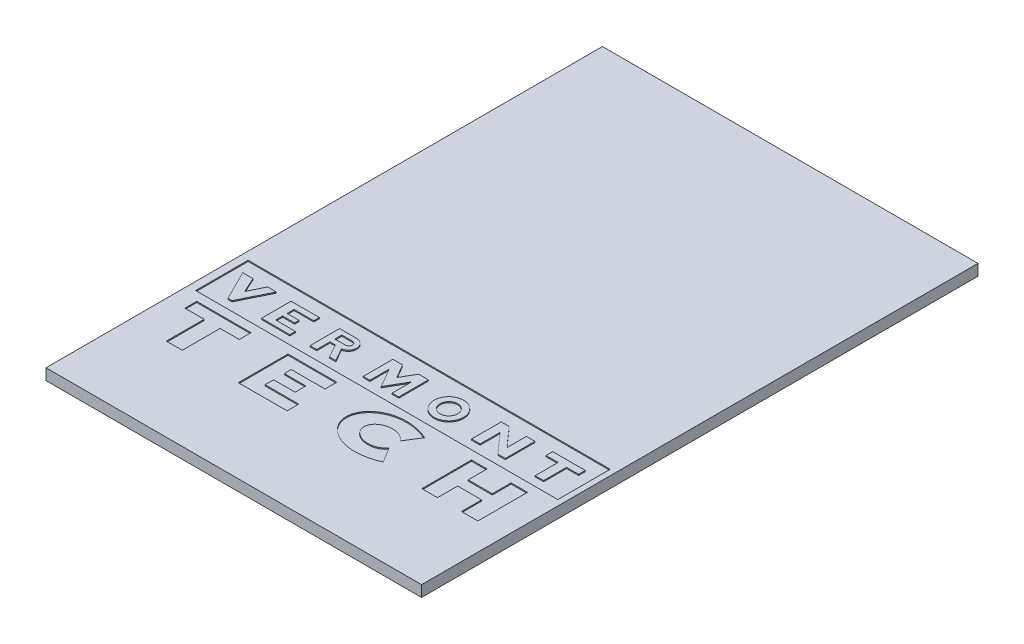
SolidWorks part; units mm, degrees
ref_plane "Front Plane" through (0, 0, 0) normal (0, 0, 1) x (1, 0, 0)
ref_plane "Top Plane" through (0, 0, 0) normal (0, 1, 0) x (1, 0, 0)
ref_plane "Right Plane" through (0, 0, 0) normal (1, 0, 0) x (0, 0, -1)
sketch "Sketch1" plane through (0, 0, 0) normal (0, 1, 0) x (1, 0, 0)
  line L1 (-42.8625, -63.5) -> (42.8625, -63.5) construction
  line L2 (-42.8625, -63.5) -> (-42.8625, 63.5) construction
  line L3 (-42.8625, 63.5) -> (42.8625, 63.5) construction
  line L4 (42.8625, -63.5) -> (42.8625, 63.5) construction
  line L5 (-42.8625, -63.5) -> (42.8625, 63.5) construction
  line L6 (-42.8625, 63.5) -> (42.8625, -63.5) construction
  line L7 (0, 0) -> (0, 63.5) construction
  point P0 (0, 0)
  dimension "D1" = 85.725
  dimension "D2" = 127
sketch "Sketch2" plane through (0, 0, 0) normal (0, 1, 0) x (1, 0, 0)
  line L0 (-42.8625, -63.5) -> (-42.8625, 63.5) construction
  line L1 (-42.8625, 63.5) -> (42.8625, 63.5) construction
  line L2 (42.8625, -63.5) -> (42.8625, 63.5) construction
  line L3 (-42.8625, -63.5) -> (42.8625, -63.5) construction
  line L4 (-42.8625, -63.5) -> (-42.8625, 63.5)
  line L5 (-42.8625, 63.5) -> (42.8625, 63.5)
  line L6 (42.8625, -63.5) -> (42.8625, 63.5)
  line L7 (-42.8625, -63.5) -> (42.8625, -63.5)
extrude "Boss-Extrude2" add sketch "Sketch2" against normal blind 2.54
sketch "Sketch17" plane through (0, 0, 0) normal (0, 1, 0) x (1, 0, 0)
  line L0 (-29.0853, 54.0966) -> (-29.424, 55.1126)
  line L1 (-29.424, 55.1126) -> (-30.1013, 56.0608)
  line L2 (-30.1013, 56.0608) -> (-30.7109, 56.535)
  line L3 (-30.7109, 56.535) -> (-31.9978, 56.535)
  line L4 (-31.9978, 56.535) -> (-32.6752, 56.0608)
  line L5 (-32.6752, 56.0608) -> (-33.2848, 55.1126)
  line L6 (-33.2848, 55.1126) -> (-33.6234, 54.0966)
  line L7 (-33.6234, 54.0966) -> (-33.9621, 52.6742)
  line L8 (-33.9621, 52.6742) -> (-33.9621, 50.2358)
  line L9 (-33.9621, 50.2358) -> (-33.6234, 48.8134)
  line L10 (-33.6234, 48.8134) -> (-33.2848, 47.7974)
  line L11 (-33.2848, 47.7974) -> (-32.6752, 46.8491)
  line L12 (-32.6752, 46.8491) -> (-31.9978, 46.375)
  line L13 (-31.9978, 46.375) -> (-30.7109, 46.375)
  line L14 (-30.7109, 46.375) -> (-30.1013, 46.8491)
  line L15 (-30.1013, 46.8491) -> (-29.424, 47.7974)
  line L16 (-29.424, 47.7974) -> (-29.0853, 48.8134)
  line L17 (-23.328, 53.1483) -> (-23.328, 46.375)
  line L18 (-23.328, 51.7259) -> (-23.9376, 52.6742)
  line L19 (-23.9376, 52.6742) -> (-24.6149, 53.1483)
  line L20 (-24.6149, 53.1483) -> (-25.5632, 53.1483)
  line L21 (-25.5632, 53.1483) -> (-26.1728, 52.6742)
  line L22 (-26.1728, 52.6742) -> (-26.8501, 51.7259)
  line L23 (-26.8501, 51.7259) -> (-27.1888, 50.2358)
  line L24 (-27.1888, 50.2358) -> (-27.1888, 49.2875)
  line L25 (-27.1888, 49.2875) -> (-26.8501, 47.7974)
  line L26 (-26.8501, 47.7974) -> (-26.1728, 46.8491)
  line L27 (-26.1728, 46.8491) -> (-25.5632, 46.375)
  line L28 (-25.5632, 46.375) -> (-24.6149, 46.375)
  line L29 (-24.6149, 46.375) -> (-23.9376, 46.8491)
  line L30 (-23.9376, 46.8491) -> (-23.328, 47.7974)
  line L31 (-20.7541, 53.1483) -> (-20.7541, 46.375)
  line L32 (-20.7541, 50.2358) -> (-20.4154, 51.7259)
  line L33 (-20.4154, 51.7259) -> (-19.8058, 52.6742)
  line L34 (-19.8058, 52.6742) -> (-19.1285, 53.1483)
  line L35 (-19.1285, 53.1483) -> (-18.1802, 53.1483)
  line L36 (-16.216, 56.535) -> (-16.216, 48.3392)
  line L37 (-16.216, 48.3392) -> (-15.8773, 46.8491)
  line L38 (-15.8773, 46.8491) -> (-15.2677, 46.375)
  line L39 (-15.2677, 46.375) -> (-14.5904, 46.375)
  line L40 (-17.1642, 53.1483) -> (-14.929, 53.1483)
  line L41 (-13.0325, 50.2358) -> (-9.1717, 50.2358)
  line L42 (-9.1717, 50.2358) -> (-9.1717, 51.184)
  line L43 (-9.1717, 51.184) -> (-9.4426, 52.2)
  line L44 (-9.4426, 52.2) -> (-9.7813, 52.6742)
  line L45 (-9.7813, 52.6742) -> (-10.4586, 53.1483)
  line L46 (-10.4586, 53.1483) -> (-11.4069, 53.1483)
  line L47 (-11.4069, 53.1483) -> (-12.0165, 52.6742)
  line L48 (-12.0165, 52.6742) -> (-12.6938, 51.7259)
  line L49 (-12.6938, 51.7259) -> (-13.0325, 50.2358)
  line L50 (-13.0325, 50.2358) -> (-13.0325, 49.2875)
  line L51 (-13.0325, 49.2875) -> (-12.6938, 47.7974)
  line L52 (-12.6938, 47.7974) -> (-12.0165, 46.8491)
  line L53 (-12.0165, 46.8491) -> (-11.4069, 46.375)
  line L54 (-11.4069, 46.375) -> (-10.4586, 46.375)
  line L55 (-10.4586, 46.375) -> (-9.7813, 46.8491)
  line L56 (-9.7813, 46.8491) -> (-9.1717, 47.7974)
  line L57 (-6.8688, 53.1483) -> (-6.8688, 46.375)
  line L58 (-6.8688, 50.2358) -> (-6.5301, 51.7259)
  line L59 (-6.5301, 51.7259) -> (-5.9205, 52.6742)
  line L60 (-5.9205, 52.6742) -> (-5.2432, 53.1483)
  line L61 (-5.2432, 53.1483) -> (-4.2949, 53.1483)
  line L62 (2.4784, 56.535) -> (2.4784, 46.375)
  line L63 (2.4784, 56.535) -> (5.0523, 46.375)
  line L64 (7.6262, 56.535) -> (5.0523, 46.375)
  line L65 (7.6262, 56.535) -> (7.6262, 46.375)
  line L66 (9.8614, 50.2358) -> (13.7222, 50.2358)
  line L67 (13.7222, 50.2358) -> (13.7222, 51.184)
  line L68 (13.7222, 51.184) -> (13.4512, 52.2)
  line L69 (13.4512, 52.2) -> (13.1126, 52.6742)
  line L70 (13.1126, 52.6742) -> (12.4352, 53.1483)
  line L71 (12.4352, 53.1483) -> (11.487, 53.1483)
  line L72 (11.487, 53.1483) -> (10.8774, 52.6742)
  line L73 (10.8774, 52.6742) -> (10.2, 51.7259)
  line L74 (10.2, 51.7259) -> (9.8614, 50.2358)
  line L75 (9.8614, 50.2358) -> (9.8614, 49.2875)
  line L76 (9.8614, 49.2875) -> (10.2, 47.7974)
  line L77 (10.2, 47.7974) -> (10.8774, 46.8491)
  line L78 (10.8774, 46.8491) -> (11.487, 46.375)
  line L79 (11.487, 46.375) -> (12.4352, 46.375)
  line L80 (12.4352, 46.375) -> (13.1126, 46.8491)
  line L81 (13.1126, 46.8491) -> (13.7222, 47.7974)
  line L82 (19.5472, 53.1483) -> (19.5472, 46.375)
  line L83 (19.5472, 51.7259) -> (18.9376, 52.6742)
  line L84 (18.9376, 52.6742) -> (18.2603, 53.1483)
  line L85 (18.2603, 53.1483) -> (17.312, 53.1483)
  line L86 (17.312, 53.1483) -> (16.7024, 52.6742)
  line L87 (16.7024, 52.6742) -> (16.0251, 51.7259)
  line L88 (16.0251, 51.7259) -> (15.6864, 50.2358)
  line L89 (15.6864, 50.2358) -> (15.6864, 49.2875)
  line L90 (15.6864, 49.2875) -> (16.0251, 47.7974)
  line L91 (16.0251, 47.7974) -> (16.7024, 46.8491)
  line L92 (16.7024, 46.8491) -> (17.312, 46.375)
  line L93 (17.312, 46.375) -> (18.2603, 46.375)
  line L94 (18.2603, 46.375) -> (18.9376, 46.8491)
  line L95 (18.9376, 46.8491) -> (19.5472, 47.7974)
  line L96 (22.1211, 56.535) -> (22.1211, 46.375)
  line L97 (24.3563, 50.2358) -> (28.2171, 50.2358)
  line L98 (28.2171, 50.2358) -> (28.2171, 51.184)
  line L99 (28.2171, 51.184) -> (27.9462, 52.2)
  line L100 (27.9462, 52.2) -> (27.6075, 52.6742)
  line L101 (27.6075, 52.6742) -> (26.9302, 53.1483)
  line L102 (26.9302, 53.1483) -> (25.9819, 53.1483)
  line L103 (25.9819, 53.1483) -> (25.3723, 52.6742)
  line L104 (25.3723, 52.6742) -> (24.695, 51.7259)
  line L105 (24.695, 51.7259) -> (24.3563, 50.2358)
  line L106 (24.3563, 50.2358) -> (24.3563, 49.2875)
  line L107 (24.3563, 49.2875) -> (24.695, 47.7974)
  line L108 (24.695, 47.7974) -> (25.3723, 46.8491)
  line L109 (25.3723, 46.8491) -> (25.9819, 46.375)
  line L110 (25.9819, 46.375) -> (26.9302, 46.375)
  line L111 (26.9302, 46.375) -> (27.6075, 46.8491)
  line L112 (27.6075, 46.8491) -> (28.2171, 47.7974)
  line L113 (29.9104, 53.1483) -> (31.807, 46.375)
  line L114 (33.7712, 53.1483) -> (31.807, 46.375)
  line L115 (31.807, 46.375) -> (31.1974, 44.4107)
  line L116 (31.1974, 44.4107) -> (30.52, 43.4624)
  line L117 (30.52, 43.4624) -> (29.9104, 43.056)
  line L118 (29.9104, 43.056) -> (29.5718, 43.056)
sketch "Sketch18" plane through (0, 0, 0) normal (0, 1, 0) x (1, 0, 0)
  line L0 (-30.7518, 39.376) -> (-30.7518, 29.216)
  line L1 (-30.7518, 39.376) -> (-27.8392, 39.376)
  line L2 (-27.8392, 39.376) -> (-26.891, 38.9019)
  line L3 (-26.891, 38.9019) -> (-26.5523, 38.4277)
  line L4 (-26.5523, 38.4277) -> (-26.2136, 37.4117)
  line L5 (-26.2136, 37.4117) -> (-26.2136, 36.4635)
  line L6 (-26.2136, 36.4635) -> (-26.5523, 35.5152)
  line L7 (-26.5523, 35.5152) -> (-26.891, 35.0411)
  line L8 (-26.891, 35.0411) -> (-27.8392, 34.5669)
  line L9 (-30.7518, 34.5669) -> (-27.8392, 34.5669)
  line L10 (-27.8392, 34.5669) -> (-26.891, 34.0251)
  line L11 (-26.891, 34.0251) -> (-26.5523, 33.5509)
  line L12 (-26.5523, 33.5509) -> (-26.2136, 32.6027)
  line L13 (-26.2136, 32.6027) -> (-26.2136, 31.1803)
  line L14 (-26.2136, 31.1803) -> (-26.5523, 30.1643)
  line L15 (-26.5523, 30.1643) -> (-26.891, 29.6901)
  line L16 (-26.891, 29.6901) -> (-27.8392, 29.216)
  line L17 (-27.8392, 29.216) -> (-30.7518, 29.216)
  line L18 (-24.3171, 33.0768) -> (-20.4563, 33.0768)
  line L19 (-20.4563, 33.0768) -> (-20.4563, 34.0251)
  line L20 (-20.4563, 34.0251) -> (-20.7272, 35.0411)
  line L21 (-20.7272, 35.0411) -> (-21.0659, 35.5152)
  line L22 (-21.0659, 35.5152) -> (-21.7432, 35.9893)
  line L23 (-21.7432, 35.9893) -> (-22.6915, 35.9893)
  line L24 (-22.6915, 35.9893) -> (-23.3011, 35.5152)
  line L25 (-23.3011, 35.5152) -> (-23.9784, 34.5669)
  line L26 (-23.9784, 34.5669) -> (-24.3171, 33.0768)
  line L27 (-24.3171, 33.0768) -> (-24.3171, 32.1285)
  line L28 (-24.3171, 32.1285) -> (-23.9784, 30.6384)
  line L29 (-23.9784, 30.6384) -> (-23.3011, 29.6901)
  line L30 (-23.3011, 29.6901) -> (-22.6915, 29.216)
  line L31 (-22.6915, 29.216) -> (-21.7432, 29.216)
  line L32 (-21.7432, 29.216) -> (-21.0659, 29.6901)
  line L33 (-21.0659, 29.6901) -> (-20.4563, 30.6384)
  line L34 (-18.1534, 35.9893) -> (-18.1534, 29.216)
  line L35 (-18.1534, 34.0251) -> (-17.2051, 35.5152)
  line L36 (-17.2051, 35.5152) -> (-16.5278, 35.9893)
  line L37 (-16.5278, 35.9893) -> (-15.5795, 35.9893)
  line L38 (-15.5795, 35.9893) -> (-14.9022, 35.5152)
  line L39 (-14.9022, 35.5152) -> (-14.6312, 34.0251)
  line L40 (-14.6312, 34.0251) -> (-14.6312, 29.216)
  line L41 (-6.9096, 39.376) -> (-6.9096, 29.216)
  line L42 (-2.3715, 39.376) -> (-2.3715, 29.216)
  line L43 (-6.9096, 34.5669) -> (-2.3715, 34.5669)
  line L44 (1.4893, 35.9893) -> (0.8797, 35.5152)
  line L45 (0.8797, 35.5152) -> (0.2024, 34.5669)
  line L46 (0.2024, 34.5669) -> (-0.1363, 33.0768)
  line L47 (-0.1363, 33.0768) -> (-0.1363, 32.1285)
  line L48 (-0.1363, 32.1285) -> (0.2024, 30.6384)
  line L49 (0.2024, 30.6384) -> (0.8797, 29.6901)
  line L50 (0.8797, 29.6901) -> (1.4893, 29.216)
  line L51 (1.4893, 29.216) -> (2.4376, 29.216)
  line L52 (2.4376, 29.216) -> (3.1149, 29.6901)
  line L53 (3.1149, 29.6901) -> (3.7245, 30.6384)
  line L54 (3.7245, 30.6384) -> (4.0632, 32.1285)
  line L55 (4.0632, 32.1285) -> (4.0632, 33.0768)
  line L56 (4.0632, 33.0768) -> (3.7245, 34.5669)
  line L57 (3.7245, 34.5669) -> (3.1149, 35.5152)
  line L58 (3.1149, 35.5152) -> (2.4376, 35.9893)
  line L59 (2.4376, 35.9893) -> (1.4893, 35.9893)
  line L60 (6.2984, 39.376) -> (6.2984, 29.216)
  line L61 (8.8722, 39.376) -> (8.8722, 29.216)
  line L62 (11.1074, 33.0768) -> (14.9682, 33.0768)
  line L63 (14.9682, 33.0768) -> (14.9682, 34.0251)
  line L64 (14.9682, 34.0251) -> (14.6973, 35.0411)
  line L65 (14.6973, 35.0411) -> (14.3586, 35.5152)
  line L66 (14.3586, 35.5152) -> (13.6813, 35.9893)
  line L67 (13.6813, 35.9893) -> (12.733, 35.9893)
  line L68 (12.733, 35.9893) -> (12.1234, 35.5152)
  line L69 (12.1234, 35.5152) -> (11.4461, 34.5669)
  line L70 (11.4461, 34.5669) -> (11.1074, 33.0768)
  line L71 (11.1074, 33.0768) -> (11.1074, 32.1285)
  line L72 (11.1074, 32.1285) -> (11.4461, 30.6384)
  line L73 (11.4461, 30.6384) -> (12.1234, 29.6901)
  line L74 (12.1234, 29.6901) -> (12.733, 29.216)
  line L75 (12.733, 29.216) -> (13.6813, 29.216)
  line L76 (13.6813, 29.216) -> (14.3586, 29.6901)
  line L77 (14.3586, 29.6901) -> (14.9682, 30.6384)
  line L78 (17.2712, 35.9893) -> (17.2712, 29.216)
  line L79 (17.2712, 33.0768) -> (17.6098, 34.5669)
  line L80 (17.6098, 34.5669) -> (18.2194, 35.5152)
  line L81 (18.2194, 35.5152) -> (18.8968, 35.9893)
  line L82 (18.8968, 35.9893) -> (19.845, 35.9893)
  line L83 (24.9928, 35.9893) -> (24.9928, 29.216)
  line L84 (24.9928, 34.5669) -> (24.3832, 35.5152)
  line L85 (24.3832, 35.5152) -> (23.7058, 35.9893)
  line L86 (23.7058, 35.9893) -> (22.7576, 35.9893)
  line L87 (22.7576, 35.9893) -> (22.148, 35.5152)
  line L88 (22.148, 35.5152) -> (21.4706, 34.5669)
  line L89 (21.4706, 34.5669) -> (21.132, 33.0768)
  line L90 (21.132, 33.0768) -> (21.132, 32.1285)
  line L91 (21.132, 32.1285) -> (21.4706, 30.6384)
  line L92 (21.4706, 30.6384) -> (22.148, 29.6901)
  line L93 (22.148, 29.6901) -> (22.7576, 29.216)
  line L94 (22.7576, 29.216) -> (23.7058, 29.216)
  line L95 (23.7058, 29.216) -> (24.3832, 29.6901)
  line L96 (24.3832, 29.6901) -> (24.9928, 30.6384)
  line L97 (27.5666, 35.9893) -> (27.5666, 29.216)
  line L98 (27.5666, 34.0251) -> (28.5149, 35.5152)
  line L99 (28.5149, 35.5152) -> (29.1922, 35.9893)
  line L100 (29.1922, 35.9893) -> (30.1405, 35.9893)
  line L101 (30.1405, 35.9893) -> (30.8178, 35.5152)
  line L102 (30.8178, 35.5152) -> (31.0888, 34.0251)
  line L103 (31.0888, 34.0251) -> (31.0888, 29.216)
sketch "Sketch20" plane through (0, 0, 0) normal (0, 1, 0) x (1, 0, 0)
  line L0 (-24.918, 18.387) -> (-24.918, 5.687)
  line L1 (-24.918, 18.387) -> (-19.6687, 18.387)
  line L2 (-24.918, 12.3757) -> (-21.7007, 12.3757)
  line L3 (-24.918, 5.687) -> (-19.6687, 5.687)
  line L4 (-17.298, 18.387) -> (-17.298, 5.687)
  line L5 (-17.298, 5.687) -> (-12.472, 5.687)
  line L6 (-8.8313, 18.387) -> (-8.8313, 5.687)
  line L7 (-11.6253, 18.387) -> (-6.0373, 18.387)
  line L8 (-0.3647, 18.387) -> (-4.4287, 9.9204)
  line L9 (-4.4287, 9.9204) -> (1.6673, 9.9204)
  line L10 (-0.3647, 18.387) -> (-0.3647, 5.687)
  line L11 (9.2873, 18.387) -> (5.2233, 5.687)
  line L12 (3.6147, 18.387) -> (9.2873, 18.387)
  line L13 (14.1133, 18.387) -> (12.928, 17.7944)
  line L14 (12.928, 17.7944) -> (12.0813, 15.9317)
  line L15 (12.0813, 15.9317) -> (11.658, 12.9684)
  line L16 (11.658, 12.9684) -> (11.658, 11.1057)
  line L17 (11.658, 11.1057) -> (12.0813, 8.1424)
  line L18 (12.0813, 8.1424) -> (12.928, 6.2797)
  line L19 (12.928, 6.2797) -> (14.1133, 5.687)
  line L20 (14.1133, 5.687) -> (14.8753, 5.687)
  line L21 (14.8753, 5.687) -> (16.1453, 6.2797)
  line L22 (16.1453, 6.2797) -> (16.9073, 8.1424)
  line L23 (16.9073, 8.1424) -> (17.3307, 11.1057)
  line L24 (17.3307, 11.1057) -> (17.3307, 12.9684)
  line L25 (17.3307, 12.9684) -> (16.9073, 15.9317)
  line L26 (16.9073, 15.9317) -> (16.1453, 17.7944)
  line L27 (16.1453, 17.7944) -> (14.8753, 18.387)
  line L28 (14.8753, 18.387) -> (14.1133, 18.387)
  line L29 (20.1247, 15.339) -> (20.1247, 15.9317)
  line L30 (20.1247, 15.9317) -> (20.548, 17.2017)
  line L31 (20.548, 17.2017) -> (20.9713, 17.7944)
  line L32 (20.9713, 17.7944) -> (21.7333, 18.387)
  line L33 (21.7333, 18.387) -> (23.342, 18.387)
  line L34 (23.342, 18.387) -> (24.1887, 17.7944)
  line L35 (24.1887, 17.7944) -> (24.5273, 17.2017)
  line L36 (24.5273, 17.2017) -> (24.9507, 15.9317)
  line L37 (24.9507, 15.9317) -> (24.9507, 14.7464)
  line L38 (24.9507, 14.7464) -> (24.5273, 13.561)
  line L39 (24.5273, 13.561) -> (23.7653, 11.6984)
  line L40 (23.7653, 11.6984) -> (19.7013, 5.687)
  line L41 (19.7013, 5.687) -> (25.374, 5.687)
sketch "Sketch23" plane through (0, 0, 0) normal (0, 1, 0) x (1, 0, 0)
  line L0 (-26.2078, -2.5254) -> (-26.8851, -1.5771)
  line L1 (-26.8851, -1.5771) -> (-27.8334, -1.103)
  line L2 (-27.8334, -1.103) -> (-29.1203, -1.103)
  line L3 (-29.1203, -1.103) -> (-30.0686, -1.5771)
  line L4 (-30.0686, -1.5771) -> (-30.7459, -2.5254)
  line L5 (-30.7459, -2.5254) -> (-30.7459, -3.5414)
  line L6 (-30.7459, -3.5414) -> (-30.4073, -4.4897)
  line L7 (-30.4073, -4.4897) -> (-30.0686, -4.9638)
  line L8 (-30.0686, -4.9638) -> (-29.459, -5.4379)
  line L9 (-29.459, -5.4379) -> (-27.4947, -6.4539)
  line L10 (-27.4947, -6.4539) -> (-26.8851, -6.9281)
  line L11 (-26.8851, -6.9281) -> (-26.5465, -7.4022)
  line L12 (-26.5465, -7.4022) -> (-26.2078, -8.3505)
  line L13 (-26.2078, -8.3505) -> (-26.2078, -9.8406)
  line L14 (-26.2078, -9.8406) -> (-26.8851, -10.7889)
  line L15 (-26.8851, -10.7889) -> (-27.8334, -11.263)
  line L16 (-27.8334, -11.263) -> (-29.1203, -11.263)
  line L17 (-29.1203, -11.263) -> (-30.0686, -10.7889)
  line L18 (-30.0686, -10.7889) -> (-30.7459, -9.8406)
  line L19 (-23.9726, -4.4897) -> (-23.9726, -14.5819)
  line L20 (-23.9726, -5.9121) -> (-23.2953, -4.9638)
  line L21 (-23.2953, -4.9638) -> (-22.6857, -4.4897)
  line L22 (-22.6857, -4.4897) -> (-21.7374, -4.4897)
  line L23 (-21.7374, -4.4897) -> (-21.0601, -4.9638)
  line L24 (-21.0601, -4.9638) -> (-20.4505, -5.9121)
  line L25 (-20.4505, -5.9121) -> (-20.1118, -7.4022)
  line L26 (-20.1118, -7.4022) -> (-20.1118, -8.3505)
  line L27 (-20.1118, -8.3505) -> (-20.4505, -9.8406)
  line L28 (-20.4505, -9.8406) -> (-21.0601, -10.7889)
  line L29 (-21.0601, -10.7889) -> (-21.7374, -11.263)
  line L30 (-21.7374, -11.263) -> (-22.6857, -11.263)
  line L31 (-22.6857, -11.263) -> (-23.2953, -10.7889)
  line L32 (-23.2953, -10.7889) -> (-23.9726, -9.8406)
  line L33 (-17.8766, -4.4897) -> (-17.8766, -11.263)
  line L34 (-17.8766, -7.4022) -> (-17.5379, -5.9121)
  line L35 (-17.5379, -5.9121) -> (-16.9283, -4.9638)
  line L36 (-16.9283, -4.9638) -> (-16.251, -4.4897)
  line L37 (-16.251, -4.4897) -> (-15.3027, -4.4897)
  line L38 (-14.0158, -1.103) -> (-13.6771, -1.5771)
  line L39 (-13.6771, -1.5771) -> (-13.3385, -1.103)
  line L40 (-13.3385, -1.103) -> (-13.6771, -0.6289)
  line L41 (-13.6771, -0.6289) -> (-14.0158, -1.103)
  line L42 (-13.6771, -4.4897) -> (-13.6771, -11.263)
  line L43 (-11.1033, -4.4897) -> (-11.1033, -11.263)
  line L44 (-11.1033, -6.4539) -> (-10.155, -4.9638)
  line L45 (-10.155, -4.9638) -> (-9.4777, -4.4897)
  line L46 (-9.4777, -4.4897) -> (-8.5294, -4.4897)
  line L47 (-8.5294, -4.4897) -> (-7.8521, -4.9638)
  line L48 (-7.8521, -4.9638) -> (-7.5811, -6.4539)
  line L49 (-7.5811, -6.4539) -> (-7.5811, -11.263)
  line L50 (-1.4851, -4.4897) -> (-1.4851, -12.2113)
  line L51 (-1.4851, -12.2113) -> (-1.7561, -13.7014)
  line L52 (-1.7561, -13.7014) -> (-2.0947, -14.1755)
  line L53 (-2.0947, -14.1755) -> (-2.7721, -14.5819)
  line L54 (-2.7721, -14.5819) -> (-3.7203, -14.5819)
  line L55 (-3.7203, -14.5819) -> (-4.3299, -14.1755)
  line L56 (-1.4851, -5.9121) -> (-2.0947, -4.9638)
  line L57 (-2.0947, -4.9638) -> (-2.7721, -4.4897)
  line L58 (-2.7721, -4.4897) -> (-3.7203, -4.4897)
  line L59 (-3.7203, -4.4897) -> (-4.3299, -4.9638)
  line L60 (-4.3299, -4.9638) -> (-5.0073, -5.9121)
  line L61 (-5.0073, -5.9121) -> (-5.3459, -7.4022)
  line L62 (-5.3459, -7.4022) -> (-5.3459, -8.3505)
  line L63 (-5.3459, -8.3505) -> (-5.0073, -9.8406)
  line L64 (-5.0073, -9.8406) -> (-4.3299, -10.7889)
  line L65 (-4.3299, -10.7889) -> (-3.7203, -11.263)
  line L66 (-3.7203, -11.263) -> (-2.7721, -11.263)
  line L67 (-2.7721, -11.263) -> (-2.0947, -10.7889)
  line L68 (-2.0947, -10.7889) -> (-1.4851, -9.8406)
  line L69 (6.2365, -3.5414) -> (6.2365, -3.0673)
  line L70 (6.2365, -3.0673) -> (6.5751, -2.0513)
  line L71 (6.5751, -2.0513) -> (6.9138, -1.5771)
  line L72 (6.9138, -1.5771) -> (7.5234, -1.103)
  line L73 (7.5234, -1.103) -> (8.8103, -1.103)
  line L74 (8.8103, -1.103) -> (9.4877, -1.5771)
  line L75 (9.4877, -1.5771) -> (9.7586, -2.0513)
  line L76 (9.7586, -2.0513) -> (10.0973, -3.0673)
  line L77 (10.0973, -3.0673) -> (10.0973, -4.0155)
  line L78 (10.0973, -4.0155) -> (9.7586, -4.9638)
  line L79 (9.7586, -4.9638) -> (9.149, -6.4539)
  line L80 (9.149, -6.4539) -> (5.8978, -11.263)
  line L81 (5.8978, -11.263) -> (10.4359, -11.263)
  line L82 (14.2967, -1.103) -> (13.3485, -1.5771)
  line L83 (13.3485, -1.5771) -> (12.6711, -3.0673)
  line L84 (12.6711, -3.0673) -> (12.3325, -5.4379)
  line L85 (12.3325, -5.4379) -> (12.3325, -6.9281)
  line L86 (12.3325, -6.9281) -> (12.6711, -9.2987)
  line L87 (12.6711, -9.2987) -> (13.3485, -10.7889)
  line L88 (13.3485, -10.7889) -> (14.2967, -11.263)
  line L89 (14.2967, -11.263) -> (14.9063, -11.263)
  line L90 (14.9063, -11.263) -> (15.9223, -10.7889)
  line L91 (15.9223, -10.7889) -> (16.5319, -9.2987)
  line L92 (16.5319, -9.2987) -> (16.8706, -6.9281)
  line L93 (16.8706, -6.9281) -> (16.8706, -5.4379)
  line L94 (16.8706, -5.4379) -> (16.5319, -3.0673)
  line L95 (16.5319, -3.0673) -> (15.9223, -1.5771)
  line L96 (15.9223, -1.5771) -> (14.9063, -1.103)
  line L97 (14.9063, -1.103) -> (14.2967, -1.103)
  line L98 (19.7831, -3.0673) -> (20.3927, -2.5254)
  line L99 (20.3927, -2.5254) -> (21.341, -1.103)
  line L100 (21.341, -1.103) -> (21.341, -11.263)
  line L101 (28.453, -1.103) -> (25.2018, -7.8763)
  line L102 (25.2018, -7.8763) -> (30.0786, -7.8763)
  line L103 (28.453, -1.103) -> (28.453, -11.263)
sketch "Logo" plane through (0, 0, 0) normal (0, 1, 0) x (1, 0, 0)
  line L0 (-27.9779, -19.17) -> (28.383, -19.17)
  line L1 (28.383, -19.17) -> (28.383, -37.7423)
  line L2 (28.383, -37.7423) -> (-27.9779, -37.7423)
  line L3 (-27.9779, -37.7423) -> (-27.9779, -19.17)
  line L4 (-25.7988, -28.4959) -> (-17.5334, -28.4959)
  line L5 (-17.5334, -28.4959) -> (-17.5334, -30.2929)
  line L6 (-17.5334, -30.2929) -> (-20.4477, -30.2929)
  line L7 (-42.8625, -63.5) -> (42.8625, 63.5) construction
  line L8 (-20.4477, -30.2929) -> (-20.4477, -36.0497)
  line L9 (-20.4477, -36.0497) -> (-22.8676, -36.0497)
  line L10 (-22.8676, -36.0497) -> (-22.8676, -30.2929)
  line L11 (-22.8676, -30.2929) -> (-25.7988, -30.2929)
  line L12 (-25.7988, -30.2929) -> (-25.7988, -28.4959)
  line L13 (-11.9087, -28.4959) -> (-4.486, -28.4959)
  line L14 (-4.486, -28.4959) -> (-4.486, -30.2929)
  line L15 (-4.486, -30.2929) -> (-9.6112, -30.2929)
  line L16 (-9.6112, -30.2929) -> (-9.6112, -31.3492)
  line L17 (-9.6112, -31.3492) -> (-6.3368, -31.3492)
  line L18 (-6.3368, -31.3492) -> (-6.3368, -32.9864)
  line L19 (-6.3368, -32.9864) -> (-9.6112, -32.9864)
  line L20 (-9.6112, -32.9864) -> (-9.6112, -34.2804)
  line L21 (-9.6112, -34.2804) -> (-4.4883, -34.2804)
  line L22 (-4.4883, -34.2804) -> (-4.4883, -36.0497)
  line L23 (-4.4883, -36.0497) -> (-11.9087, -36.0497)
  line L24 (-11.9087, -36.0497) -> (-11.9087, -28.4959)
  line L25 (9.5073, -29.1483) -> (8.0907, -31.3991)
  line L26 (8.137, -33.1643) -> (9.5622, -35.4572)
  line L27 (16.0152, -28.4959) -> (16.0152, -36.0497)
  line L28 (16.0152, -36.0497) -> (18.3956, -36.0497)
  line L29 (18.3956, -36.0497) -> (18.3956, -32.9864)
  line L30 (18.3956, -32.9864) -> (22.04, -32.9864)
  line L31 (22.04, -32.9864) -> (22.04, -36.0497)
  line L32 (22.04, -36.0497) -> (24.5344, -36.0497)
  line L33 (24.5344, -36.0497) -> (24.5344, -28.4959)
  line L34 (24.5344, -28.4959) -> (22.04, -28.4959)
  line L35 (22.04, -28.4959) -> (22.04, -31.366)
  line L36 (22.04, -31.366) -> (18.3806, -31.366)
  line L37 (18.3806, -31.366) -> (18.3806, -28.4959)
  line L38 (18.3806, -28.4959) -> (16.0152, -28.4959)
  line L39 (-27.3012, -19.17) -> (27.7955, -19.17)
  line L40 (27.7955, -19.17) -> (27.7955, -27.1525)
  line L41 (27.7955, -27.1525) -> (-27.3012, -27.1525)
  line L42 (-27.3012, -27.1525) -> (-27.3012, -19.17)
  line L43 (-26.0673, -21.2195) -> (-24.5063, -21.2195)
  line L44 (-24.5063, -21.2195) -> (-23.4501, -23.5522)
  line L45 (-23.4501, -23.5522) -> (-22.3001, -21.2195)
  line L46 (-22.3001, -21.2195) -> (-20.9884, -21.2195)
  line L47 (-20.9884, -21.2195) -> (-23.2071, -25.7199)
  line L48 (-23.2071, -25.7199) -> (-23.8175, -25.7199)
  line L49 (-23.8175, -25.7199) -> (-26.0673, -21.2195)
  line L50 (-18.6345, -21.2195) -> (-14.3232, -21.2195)
  line L51 (-14.3232, -21.2195) -> (-14.3232, -22.0348)
  line L52 (-14.3232, -22.0348) -> (-17.3101, -22.0348)
  line L53 (-17.3101, -22.0348) -> (-17.3101, -22.9574)
  line L54 (-17.3101, -22.9574) -> (-15.4962, -22.9574)
  line L55 (-15.4962, -22.9574) -> (-15.4962, -23.8071)
  line L56 (-15.4962, -23.8071) -> (-17.2986, -23.8071)
  line L57 (-17.2986, -23.8071) -> (-17.2986, -24.7407)
  line L58 (-17.2986, -24.7407) -> (-14.3232, -24.7407)
  line L59 (-14.3232, -24.7407) -> (-14.3232, -25.7199)
  line L60 (-14.3232, -25.7199) -> (-18.6345, -25.7199)
  line L61 (-18.6345, -25.7199) -> (-18.6345, -21.2195)
  line L62 (-7.4104, -25.7199) -> (-8.5236, -23.7558)
  line L63 (-7.4104, -25.7199) -> (-8.3634, -25.7199)
  line L64 (-8.3634, -25.7199) -> (-9.5125, -23.6924)
  line L65 (-9.5125, -23.6924) -> (-10.3249, -23.6924)
  line L66 (-10.3249, -23.6924) -> (-10.3249, -25.7199)
  line L67 (-10.3249, -25.7199) -> (-11.3387, -25.7199)
  line L68 (-11.3387, -25.7199) -> (-11.3387, -21.2195)
  line L69 (-11.3387, -21.2195) -> (-8.7296, -21.2195)
  line L70 (-10.3249, -22.0348) -> (-8.7296, -22.0348)
  line L72 (-8.7296, -22.9574) -> (-10.3249, -22.9574)
  line L73 (-10.3249, -22.9574) -> (-10.3249, -22.0348)
  line L74 (-3.2401, -21.2195) -> (-1.7443, -21.2195)
  line L75 (-1.7443, -21.2195) -> (-0.5323, -23.3188)
  line L76 (-0.5323, -23.3188) -> (0.6797, -21.2195)
  line L77 (0.6797, -21.2195) -> (2.1755, -21.2195)
  line L78 (2.1755, -21.2195) -> (2.1755, -25.7199)
  line L79 (2.1755, -25.7199) -> (1.16, -25.7199)
  line L80 (1.16, -25.7199) -> (1.16, -22.7677)
  line L81 (1.16, -22.7677) -> (-0.5323, -25.699)
  line L82 (-0.5323, -25.699) -> (-2.2247, -22.7677)
  line L83 (-2.2247, -22.7677) -> (-2.2247, -25.7199)
  line L84 (-2.2247, -25.7199) -> (-3.2401, -25.7199)
  line L85 (-3.2401, -25.7199) -> (-3.2401, -21.2195)
  line L86 (13.2544, -25.7199) -> (13.2544, -21.2195)
  line L87 (13.2544, -21.2195) -> (14.4743, -21.2195)
  line L88 (14.4743, -21.2195) -> (17.0831, -24.1828)
  line L89 (17.0831, -24.1828) -> (17.0831, -21.2195)
  line L90 (17.0831, -21.2195) -> (18.3831, -21.2195)
  line L91 (18.3831, -21.2195) -> (18.3831, -25.7199)
  line L92 (18.3831, -25.7199) -> (17.2332, -25.7199)
  line L93 (17.2332, -25.7199) -> (14.5544, -22.6771)
  line L94 (14.5544, -22.6771) -> (14.5544, -25.7199)
  line L95 (14.5544, -25.7199) -> (13.2544, -25.7199)
  line L96 (21.0894, -21.2195) -> (26.046, -21.2195)
  line L97 (26.046, -21.2195) -> (26.046, -22.2373)
  line L98 (26.046, -22.2373) -> (24.2103, -22.2373)
  line L99 (24.2103, -22.2373) -> (24.2103, -25.7199)
  line L100 (24.2103, -25.7199) -> (22.925, -25.7199)
  line L101 (22.925, -25.7199) -> (22.925, -22.2373)
  line L102 (22.925, -22.2373) -> (21.0894, -22.2373)
  line L103 (21.0894, -22.2373) -> (21.0894, -21.2195)
  line L104 (-2.2247, -25.7199) -> (1.16, -25.7199) construction
  line L105 (-0.5323, -25.7199) -> (-0.5323, -25.699) construction
  line L106 (-0.5323, -23.3188) -> (-0.5323, -25.699) construction
  arc A0 (-8.5236, -23.7558) -> (-8.7296, -21.2195) centre (-8.7296, -22.4961) ccw
  circle A1 centre (7.5419, -23.4697) radius 1.3442
  circle A2 centre (7.5419, -23.4697) radius 2.2502
  arc A3 (-8.7296, -22.9574) -> (-8.7296, -22.0348) centre (-8.7296, -22.4961) ccw
  ellipse E0 centre (5.9198, -32.3033) end of major axis (11.8676, -32.3433) minor radius 3.9723 (5.8931, -36.2755) -> (9.5622, -35.4572) ccw
  ellipse E1 centre (5.9198, -32.3033) end of major axis (3.4414, -32.27) minor radius 1.8986 (8.0907, -31.3991) -> (8.137, -33.1643) ccw
  ellipse E2 centre (5.9198, -32.3033) end of major axis (11.0782, -32.338) minor radius 3.9723 (5.9465, -28.3311) -> (5.8931, -36.2755) ccw
  ellipse E3 centre (5.9198, -32.3033) end of major axis (11.8676, -32.3433) minor radius 3.9723 (9.5073, -29.1483) -> (5.9465, -28.3311) ccw
sketch "Sketch25" plane through (0, 0, 0) normal (0, 1, 0) x (1, 0, 0)
  line L16 (-26.4013, -33.1588) -> (-38.7995, -33.1588)
  line L17 (-26.4013, -35.8544) -> (-26.4013, -33.1588)
  line L18 (-30.7729, -35.8544) -> (-26.4013, -35.8544)
  line L19 (-30.7729, -44.4895) -> (-30.7729, -35.8544)
  line L20 (-34.4027, -44.4895) -> (-30.7729, -44.4895)
  line L21 (-34.4027, -35.8544) -> (-34.4027, -44.4895)
  line L22 (-38.7995, -35.8544) -> (-34.4027, -35.8544)
  line L23 (-38.7995, -33.1588) -> (-38.7995, -35.8544)
  line L24 (42.4732, -19.17) -> (-42.0681, -19.17)
  line L25 (42.4732, -47.0284) -> (42.4732, -19.17)
  line L26 (-42.0681, -47.0284) -> (42.4732, -47.0284)
  line L27 (-42.0681, -19.17) -> (-42.0681, -47.0284)
  line L32 (41.5919, -19.17) -> (-41.0531, -19.17)
  line L33 (41.5919, -31.1437) -> (41.5919, -19.17)
  line L34 (-41.0531, -31.1437) -> (41.5919, -31.1437)
  line L35 (-41.0531, -19.17) -> (-41.0531, -31.1437)
  line L48 (-14.5181, -35.8544) -> (-6.8303, -35.8544)
  line L49 (-14.5181, -37.4388) -> (-14.5181, -35.8544)
  line L50 (-9.6064, -37.4388) -> (-14.5181, -37.4388)
  line L51 (-9.6064, -39.8947) -> (-9.6064, -37.4388)
  line L52 (-14.5181, -39.8947) -> (-9.6064, -39.8947)
  line L53 (-14.5181, -41.8356) -> (-14.5181, -39.8947)
  line L54 (-6.8337, -41.8356) -> (-14.5181, -41.8356)
  line L55 (-6.8337, -44.4895) -> (-6.8337, -41.8356)
  line L56 (-17.9643, -44.4895) -> (-6.8337, -44.4895)
  line L57 (-17.9643, -33.1588) -> (-17.9643, -44.4895)
  line L58 (-6.8303, -33.1588) -> (-17.9643, -33.1588)
  line L59 (-6.8303, -35.8544) -> (-6.8303, -33.1588)
  line L62 (-13.1957, -23.2509) -> (-15.5887, -23.2509)
  line L80 (23.9215, -44.4895) -> (27.4922, -44.4895)
  line L81 (27.4922, -44.4895) -> (27.4922, -39.8947)
  line L82 (27.4922, -39.8947) -> (32.9587, -39.8947)
  line L83 (32.9587, -39.8947) -> (32.9587, -44.4895)
  line L84 (32.9587, -44.4895) -> (36.7003, -44.4895)
  line L85 (36.7003, -44.4895) -> (36.7003, -33.1588)
  line L86 (36.7003, -33.1588) -> (32.9587, -33.1588)
  line L87 (32.9587, -33.1588) -> (32.9587, -37.464)
  line L88 (32.9587, -37.464) -> (27.4696, -37.464)
  line L89 (27.4696, -37.464) -> (27.4696, -33.1588)
  line L90 (27.4696, -33.1588) -> (23.9215, -33.1588)
  line L91 (23.9215, -33.1588) -> (23.9215, -44.4895)
  line L94 (-35.2765, -25.7433) -> (-36.8607, -22.2443)
  line L95 (-33.5515, -22.2443) -> (-35.2765, -25.7433)
  line L96 (-31.5839, -22.2443) -> (-33.5515, -22.2443)
  line L97 (-34.9119, -28.9948) -> (-31.5839, -22.2443)
  line L98 (-35.8276, -28.9948) -> (-34.9119, -28.9948)
  line L99 (-39.2023, -22.2443) -> (-35.8276, -28.9948)
  line L100 (-36.8607, -22.2443) -> (-39.2023, -22.2443)
  line L101 (-15.5887, -24.8511) -> (-13.1957, -24.8511)
  line L102 (-15.5887, -23.2509) -> (-15.5887, -24.8511)
  line L104 (12.0347, -37.5137) -> (14.1597, -34.1374)
  line L105 (14.242, -43.6008) -> (12.1042, -40.1614)
  line L116 (-11.2169, -28.9948) -> (-12.8866, -26.0488)
  line L117 (-13.1957, -22.2443) -> (-17.1093, -22.2443)
  line L118 (-17.1093, -22.2443) -> (-17.1093, -28.9948)
  line L119 (-17.1093, -28.9948) -> (-15.5887, -28.9948)
  line L120 (-15.5887, -28.9948) -> (-15.5887, -25.9535)
  line L121 (-15.5887, -25.9535) -> (-14.3701, -25.9535)
  line L122 (-14.3701, -25.9535) -> (-12.6464, -28.9948)
  line L123 (-12.6464, -28.9948) -> (-11.2169, -28.9948)
  line L140 (-28.053, -29.1216) -> (-21.5861, -29.1216)
  line L141 (-28.053, -22.3711) -> (-28.053, -29.1216)
  line L142 (-21.6111, -22.3711) -> (-28.053, -22.3711)
  line L143 (-21.6111, -23.6382) -> (-21.6111, -22.3711)
  line L144 (-26.0914, -23.6382) -> (-21.6111, -23.6382)
  line L145 (-26.0914, -25.2384) -> (-26.0914, -23.6382)
  line L146 (-23.3697, -25.2384) -> (-26.0914, -25.2384)
  line L147 (-23.3697, -26.2544) -> (-23.3697, -25.2384)
  line L148 (-26.094, -26.2544) -> (-23.3697, -26.2544)
  line L149 (-26.094, -27.8546) -> (-26.094, -26.2544)
  line L150 (-21.5861, -27.8546) -> (-26.094, -27.8546)
  line L151 (-21.5861, -29.1216) -> (-21.5861, -27.8546)
  line L164 (-2.7178, -22.2443) -> (-4.9615, -22.2443)
  line L165 (-0.8998, -25.3932) -> (-2.7178, -22.2443)
  line L166 (0.9182, -22.2443) -> (-0.8998, -25.3932)
  line L167 (3.1619, -22.2443) -> (0.9182, -22.2443)
  line L168 (3.1619, -28.9948) -> (3.1619, -22.2443)
  line L169 (1.6388, -28.9948) -> (3.1619, -28.9948)
  line L170 (1.6388, -24.5665) -> (1.6388, -28.9948)
  line L171 (-0.8998, -28.9635) -> (1.6388, -24.5665)
  line L172 (-3.4384, -24.5665) -> (-0.8998, -28.9635)
  line L173 (-3.4384, -28.9948) -> (-3.4384, -24.5665)
  line L174 (-4.9615, -28.9948) -> (-3.4384, -28.9948)
  line L175 (-4.9615, -22.2443) -> (-4.9615, -28.9948)
  line L184 (21.6102, -22.2443) -> (19.7804, -22.2443)
  line L185 (25.5234, -26.6891) -> (21.6102, -22.2443)
  line L186 (25.5234, -22.2443) -> (25.5234, -26.6891)
  line L187 (27.4733, -22.2443) -> (25.5234, -22.2443)
  line L188 (27.4733, -28.9948) -> (27.4733, -22.2443)
  line L189 (25.7486, -28.9948) -> (27.4733, -28.9948)
  line L190 (21.7303, -24.4307) -> (25.7486, -28.9948)
  line L191 (21.7303, -28.9948) -> (21.7303, -24.4307)
  line L192 (19.7804, -28.9948) -> (21.7303, -28.9948)
  line L193 (19.7804, -22.2443) -> (19.7804, -28.9948)
  line L204 (31.5328, -23.771) -> (34.2863, -23.771)
  line L205 (34.2863, -23.771) -> (34.2863, -28.9948)
  line L206 (34.2863, -28.9948) -> (36.2142, -28.9948)
  line L207 (36.2142, -28.9948) -> (36.2142, -23.771)
  line L208 (36.2142, -23.771) -> (38.9677, -23.771)
  line L209 (38.9677, -23.771) -> (38.9677, -22.2443)
  line L210 (38.9677, -22.2443) -> (31.5328, -22.2443)
  line L211 (31.5328, -22.2443) -> (31.5328, -23.771)
  arc A2 (-13.1957, -24.8511) -> (-13.1957, -23.2509) centre (-13.1957, -24.051) ccw
  arc A4 (-12.8866, -26.0488) -> (-13.1957, -22.2443) centre (-13.1957, -24.1591) ccw
  circle A6 centre (11.2115, -25.6196) radius 3.3752
  circle A8 centre (11.2115, -25.6196) radius 2.0163
  ellipse E8 centre (8.7784, -38.87) end of major axis (1.0408, -38.818) minor radius 5.9584 (8.8185, -32.9117) -> (8.7384, -44.8282) ccw
  ellipse E9 centre (8.7784, -38.87) end of major axis (-0.1433, -38.81) minor radius 5.9584 (14.1597, -34.1374) -> (8.8185, -32.9117) ccw
  ellipse E10 centre (8.7784, -38.87) end of major axis (5.0608, -38.8201) minor radius 2.848 (12.0347, -37.5137) -> (12.1042, -40.1614) ccw
  ellipse E11 centre (8.7784, -38.87) end of major axis (-0.1433, -38.81) minor radius 5.9584 (8.7384, -44.8282) -> (14.242, -43.6008) ccw
  point P0 (0, 0)
  dimension "D1" = 1.6002
  dimension "D2" = 1.6002
  dimension "D3" = 1.016
  dimension "D4" = 6.7505
extrude "Cut-Extrude3" cut sketch "Sketch25" against normal blind 0.254 contours L16 L23 L22 L21 L20 L19 L18 L17 | L24 L35 L34 L33 A6 A4 L116 L123 L122 L121 L120 L119 L118 L117 L211 L210 L209 L208 L207 L206 L205 L204 L193 L184 L185 L186 L187 L188 L189 L190 L191 L192 L175 L164 L165 L166 L167 L168 L169 L170 L171 L172 L173 L174 L151 | L48 L59 L58 L57 L56 L55 L54 L53 L52 L51 L50 L49 | E8 E11 L105 E10 L104 E9 | L90 L91 L80 L81 L82 L83 L84 L85 L86 L87 L88 L89 | A8 | L101 A2 L62 L102
